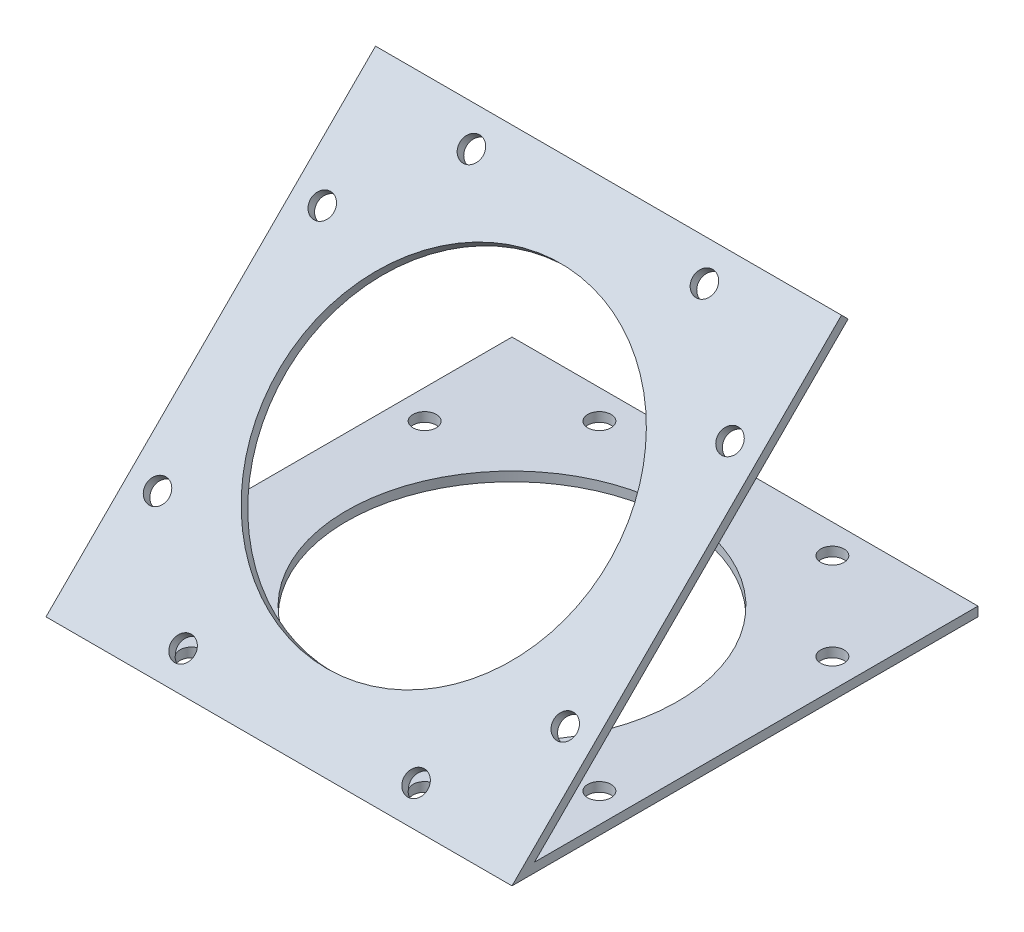
SolidWorks part; units mm, degrees
ref_plane "前视基准面" through (0, 0, 0) normal (0, 0, 1) x (1, 0, 0)
ref_plane "上视基准面" through (0, 0, 0) normal (0, 1, 0) x (1, 0, 0)
ref_plane "右视基准面" through (0, 0, 0) normal (1, 0, 0) x (0, 0, -1)
sketch "草图1" plane through (0, 0, 0) normal (1, 0, 0) x (0, 0, -1)
  line L0 (141.4214, 141.4214) -> (0, 0)
  line L1 (0, 0) -> (200, 0)
  line L2 (141.4214, 141.4214) -> (144.2498, 138.5929)
  line L3 (144.2498, 138.5929) -> (9.6569, 4)
  line L4 (9.6569, 4) -> (200, 4)
  line L5 (200, 4) -> (200, 0)
  dimension "D1" = 45
  dimension "D2" = 4
  dimension "D3" = 4
  dimension "D4" = 200
  dimension "D5" = 200
extrude "凸台-拉伸1" add sketch "草图1" along normal blind 200
sketch "草图4" plane through (0, 0, 0) normal (0, 0.7071, 0.7071) x (1, 0, 0)
  line L11 (12.5, 100) -> (187.5, 100) construction
  line L12 (100, 187.5) -> (100, 12.5) construction
  line L14 (187.5, 12.5) -> (187.5, 187.5)
  line L15 (12.5, 12.5) -> (187.5, 12.5)
  line L16 (12.5, 187.5) -> (12.5, 12.5)
  line L17 (187.5, 187.5) -> (12.5, 187.5)
  line L18 (187.5, 12.5) -> (187.5, 187.5) construction
  line L19 (12.5, 12.5) -> (187.5, 12.5) construction
  line L20 (12.5, 187.5) -> (12.5, 12.5) construction
  line L21 (187.5, 187.5) -> (12.5, 187.5) construction
  circle A0 centre (12.5, 150) radius 5
  circle A1 centre (12.5, 50) radius 5
  circle A2 centre (50, 187.5) radius 5
  circle A3 centre (150, 187.5) radius 5
  circle A4 centre (187.5, 50) radius 5
  circle A5 centre (187.5, 150) radius 5
  circle A6 centre (150, 12.5) radius 5
  circle A7 centre (50, 12.5) radius 5
  point P5 (12.5, 100)
  point P9 (100, 187.5)
  dimension "D2" = 10
  dimension "D3" = 10
  dimension "D6" = 10
  dimension "D7" = 10
  dimension "D4" = 100
  dimension "D5" = 50
  dimension "D8" = 100
  dimension "D9" = 50
  dimension "D1" = 12.5
extrude "切除-拉伸3" cut sketch "草图4" against normal blind 5
sketch "草图5" plane through (0, 0, 0) normal (0, -1, 0) x (1, 0, 0)
  line L10 (100, -12.5) -> (100, -187.5) construction
  line L11 (12.5, -100) -> (187.5, -100) construction
  line L14 (187.5, -187.5) -> (187.5, -12.5)
  line L15 (12.5, -187.5) -> (187.5, -187.5)
  line L16 (12.5, -12.5) -> (12.5, -187.5)
  line L17 (187.5, -12.5) -> (12.5, -12.5)
  line L18 (187.5, -187.5) -> (187.5, -12.5) construction
  line L19 (12.5, -187.5) -> (187.5, -187.5) construction
  line L20 (12.5, -12.5) -> (12.5, -187.5) construction
  line L21 (187.5, -12.5) -> (12.5, -12.5) construction
  circle A0 centre (12.5, -50) radius 5
  circle A1 centre (12.5, -150) radius 5
  circle A2 centre (50, -187.5) radius 5
  circle A3 centre (150, -187.5) radius 5
  circle A4 centre (150, -12.5) radius 5
  circle A5 centre (50, -12.5) radius 5
  circle A6 centre (187.5, -150) radius 5
  circle A7 centre (187.5, -50) radius 5
  dimension "D2" = 10
  dimension "D3" = 10
  dimension "D6" = 10
  dimension "D7" = 10
  dimension "D4" = 100
  dimension "D5" = 50
  dimension "D8" = 100
  dimension "D9" = 50
  dimension "D1" = 12.5
extrude "切除-拉伸4" cut sketch "草图5" against normal blind 5
sketch "草图6" plane through (0, 0, 0) normal (0, 0.7071, 0.7071) x (1, 0, 0)
  line L1 (200, 0) -> (0, 0) construction
  line L2 (200, 200) -> (200, 0) construction
  circle A0 centre (100, 100) radius 71
  dimension "D1" = 100
  dimension "D3" = 142
  dimension "D2" = 100
extrude "切除-拉伸5" cut sketch "草图6" against normal blind 10
sketch "草图7" plane through (0, 0, 0) normal (0, -1, 0) x (1, 0, 0)
  line L0 (200, 0) -> (0, 0) construction
  line L1 (200, 0) -> (200, -200) construction
  circle A0 centre (100, -100) radius 71
  dimension "D1" = 142
  dimension "D2" = 100
  dimension "D3" = 100
extrude "切除-拉伸6" cut sketch "草图7" against normal blind 10
